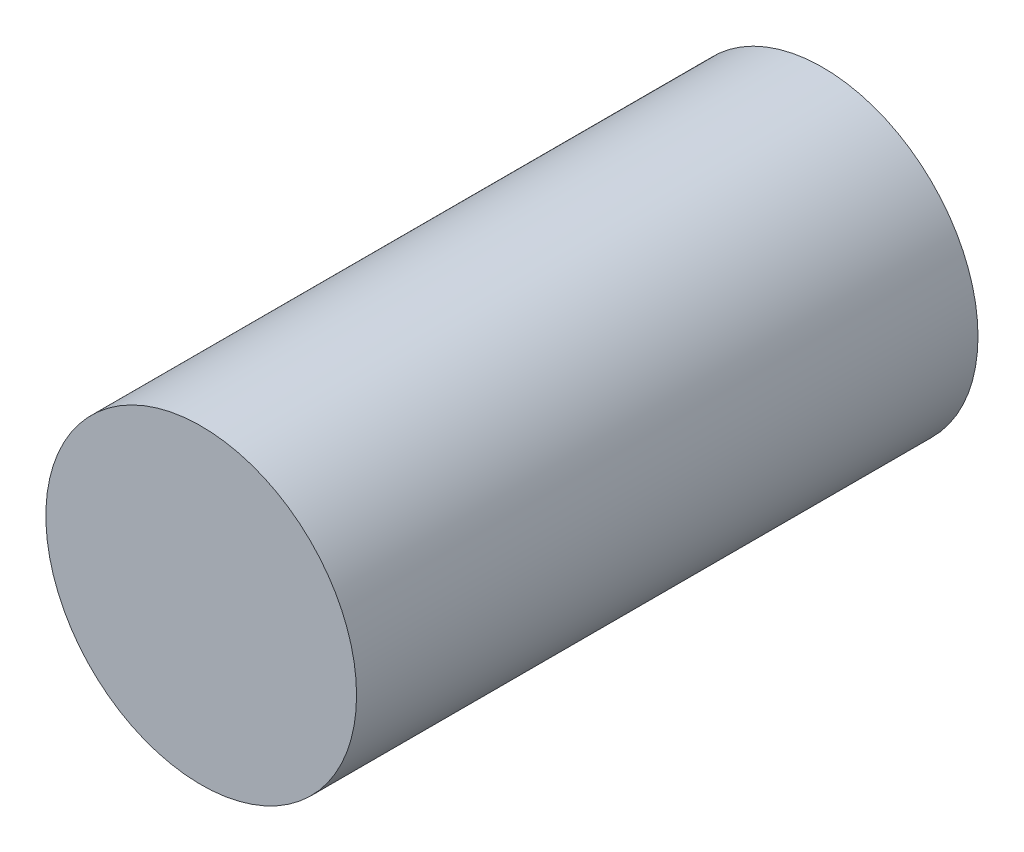
SolidWorks part; units mm, degrees
ref_plane "Front Plane" through (0, 0, 0) normal (0, 0, 1) x (1, 0, 0)
ref_plane "Top Plane" through (0, 0, 0) normal (0, 1, 0) x (1, 0, 0)
ref_plane "Right Plane" through (0, 0, 0) normal (1, 0, 0) x (0, 0, -1)
sketch "Sketch1" plane through (0, 0, 0) normal (0, 0, 1) x (1, 0, 0)
  circle A0 centre (0, 0) radius 17.5
  dimension "D1" = 35
extrude "Boss-Extrude1" add sketch "Sketch1" along normal blind 70
